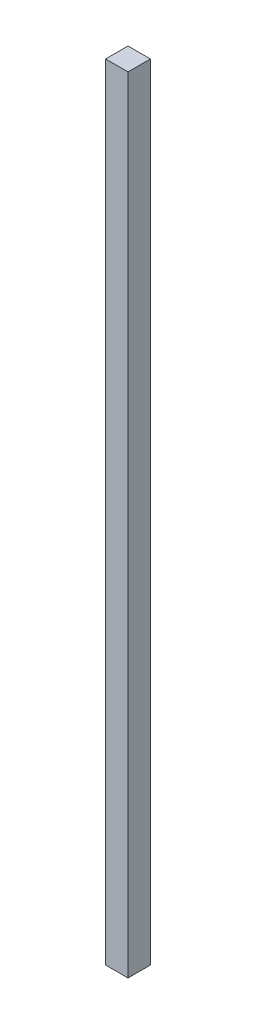
SolidWorks part; units mm, degrees
ref_plane "Front Plane" through (0, 0, 0) normal (0, 0, 1) x (1, 0, 0)
ref_plane "Top Plane" through (0, 0, 0) normal (0, 1, 0) x (1, 0, 0)
ref_plane "Right Plane" through (0, 0, 0) normal (1, 0, 0) x (0, 0, -1)
sketch "Sketch2" plane through (0, 0, 0) normal (0, 1, 0) x (1, 0, 0)
  line L1 (-10, 10) -> (10, 10)
  line L2 (-10, 10) -> (-10, -10)
  line L3 (-10, -10) -> (10, -10)
  line L4 (10, 10) -> (10, -10)
  line L5 (-10, 10) -> (10, -10) construction
  line L6 (-10, -10) -> (10, 10) construction
  point P0 (0, 0)
  dimension "D1" = 20
  dimension "D2" = 20
extrude "Boss-Extrude1" add sketch "Sketch2" along normal blind 700
